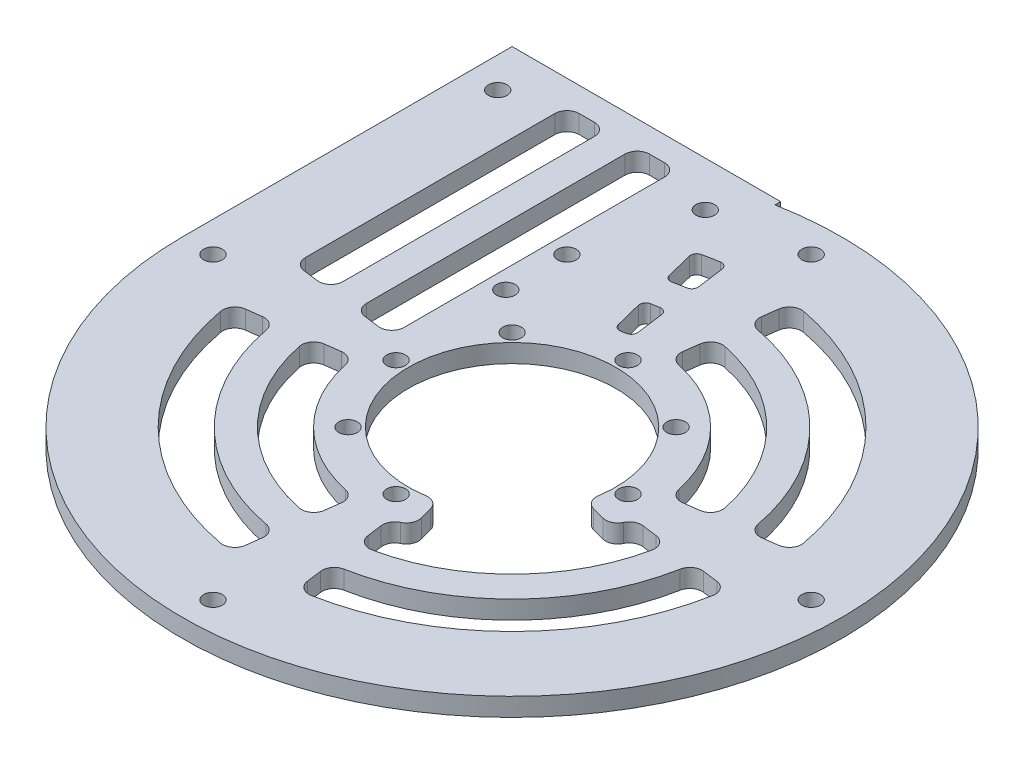
SolidWorks part; units mm, degrees
material "Thornel Mat VMA"
ref_plane "前视基准面" through (0, 0, 0) normal (0, 0, 1) x (1, 0, 0)
ref_plane "上视基准面" through (0, 0, 0) normal (0, 1, 0) x (1, 0, 0)
ref_plane "右视基准面" through (0, 0, 0) normal (1, 0, 0) x (0, 0, -1)
sketch "草图1" plane through (0, 0, 0) normal (0, 1, 0) x (1, 0, 0)
  line L0 (-54, 0) -> (-54, 54)
  line L1 (-54, 54) -> (-10, 54)
  line L2 (-10, 54) -> (-10, 53.066)
  line L3 (-32, 0) -> (-32, 54) construction
  line L4 (-15, 54) -> (-15, 46.6476) construction
  line L5 (-15, 54) -> (-15, 45.6644) construction
  line L6 (-49, 0) -> (-49, 54) construction
  line L7 (-10, 54) -> (-10, 45.6644) construction
  line L8 (-23, 0) -> (-23, 54) construction
  line L9 (-20, 28.98) -> (-20, 18.98) construction
  line L10 (-49, 46.6476) -> (-15, 46.6476) construction
  arc A0 (-54, 0) -> (-10, 53.066) centre (0, 0) ccw
  circle A1 centre (0, 0) radius 41 construction
  circle A2 centre (0, 0) radius 32 construction
  circle A3 centre (0, 0) radius 23 construction
  circle A4 centre (0, 0) radius 49 construction
  circle A5 centre (-15, 46.6476) radius 1.525
  circle A6 centre (0, 49) radius 1.525
  circle A7 centre (49, 0) radius 1.525
  circle A8 centre (0, -49) radius 1.525
  circle A9 centre (-49, 0) radius 1.525
  circle A10 centre (0, 0) radius 17
  circle A11 centre (0, 0) radius 19 construction
  circle A12 centre (0, 19) radius 1.525
  circle A13 centre (13.435, 13.435) radius 1.525
  circle A14 centre (19, 0) radius 1.525
  circle A15 centre (13.435, -13.435) radius 1.525
  circle A16 centre (0, -19) radius 1.525
  circle A17 centre (-13.435, -13.435) radius 1.525
  circle A18 centre (-19, 0) radius 1.525
  circle A19 centre (-13.435, 13.435) radius 1.525
  circle A20 centre (0, 0) radius 54 construction
  circle A21 centre (-49, 46.6476) radius 1.525
  circle A23 centre (-20, 28.98) radius 1.525
  circle A24 centre (-20, 18.98) radius 1.525
  circle A25 centre (44.7325, -20) radius 1.525 construction
  point P58 (-20, 24.98)
  dimension "D8" = 3.05
  dimension "D9" = 34
  dimension "D10" = 38
  dimension "D11" = 3.05
  dimension "D13" = 3
  dimension "D14" = 4
  dimension "D16" = 20
  dimension "D17" = 82
  dimension "D2" = 9
  dimension "D3" = 9
  dimension "D4" = 5
  dimension "D5" = 8
  dimension "D15" = 6
  dimension "D6" = 17
  dimension "D7" = 4
  dimension "D12" = 8
extrude "凸台-拉伸1" add sketch "草图1" along normal blind 3
sketch "草图2" plane through (0, 0, 0) normal (0, 1, 0) x (1, 0, 0)
  line L0 (-41, 7.1517) -> (-41, 48)
  line L1 (-39, 50) -> (-36.5, 50)
  line L2 (-23, 0) -> (-23, 54) construction
  line L3 (-23, 48) -> (-23, 5.3086)
  line L4 (-29.5, 0) -> (-29.5, 54)
  line L5 (-29.5, 5.6377) -> (-29.5, 48)
  line L6 (-34.5, 0) -> (-34.5, 54)
  line L7 (-34.5, 6.8226) -> (-34.5, 48)
  line L8 (-54, 54) -> (-10, 54) construction
  line L9 (-27.5, 50) -> (-25, 50)
  line L10 (-9.753, 38.7799) -> (-8.6551, 34.4142)
  line L11 (-3.7177, 28.2388) -> (-3.1299, 23.774)
  line L12 (0, 0) -> (-49, 0) construction
  line L13 (0, 0) -> (0, -49) construction
  line L14 (0, 0) -> (49, 0) construction
  line L15 (0, 0) -> (0, 29.5) construction
  line L16 (-5.2194, 39.6454) -> (-4.6318, 35.1823)
  line L17 (5.0838, 38.6155) -> (4.757, 36.1334)
  line L18 (-6.9469, 27.6223) -> (-5.8486, 23.255)
  line L19 (0, 34.5) -> (0, 49) construction
  line L20 (3.58, 27.1925) -> (3.2527, 24.7067)
  line L21 (38.6155, 5.0838) -> (36.1334, 4.757)
  line L22 (27.1925, 3.58) -> (24.7067, 3.2527)
  line L23 (38.6155, -5.0838) -> (36.1334, -4.757)
  line L24 (27.1925, -3.58) -> (24.7067, -3.2527)
  line L25 (5.0838, -38.6155) -> (4.757, -36.1334)
  line L26 (3.58, -27.1925) -> (3.2527, -24.7067)
  line L27 (-5.0838, -38.6155) -> (-4.757, -36.1334)
  line L28 (-3.58, -27.1925) -> (-3.2527, -24.7067)
  line L29 (-38.6155, -5.0838) -> (-36.1334, -4.757)
  line L30 (-27.1925, -3.58) -> (-24.7067, -3.2527)
  line L31 (-39.2611, 5.1688) -> (-36.7611, 4.8397)
  line L32 (-27.7611, 3.6548) -> (-25.2611, 3.3257)
  circle A0 centre (0, 0) radius 23 construction
  circle A1 centre (0, 0) radius 41 construction
  arc A2 (-22.49, -4.8167) -> (-4.8167, -22.49) centre (0, 0) ccw
  circle A3 centre (0, 0) radius 34.5
  arc A4 (-33.9067, -6.3706) -> (-6.3706, -33.9067) centre (0, 0) ccw
  circle A5 centre (0, 0) radius 29.5
  arc A6 (-28.8901, -5.9674) -> (-5.9674, -28.8901) centre (0, 0) ccw
  arc A7 (-40.3213, -7.4291) -> (-7.4291, -40.3213) centre (0, 0) ccw
  arc A8 (-6.3661, 40.5027) -> (-9.0028, 39.9994) centre (0, 0) ccw
  arc A9 (-5.4649, 34.0644) -> (-7.4688, 33.6818) centre (0, 0) ccw
  arc A10 (-4.8744, 29.0945) -> (-6.1869, 28.8439) centre (0, 0) ccw
  arc A11 (-3.9496, 22.6583) -> (-4.6755, 22.5198) centre (0, 0) ccw
  arc A12 (40.3213, 7.4291) -> (7.4291, 40.3213) centre (0, 0) ccw
  arc A13 (33.9067, 6.3706) -> (6.3706, 33.9067) centre (0, 0) ccw
  arc A14 (28.8901, 5.9674) -> (5.9674, 28.8901) centre (0, 0) ccw
  arc A15 (22.49, 4.8167) -> (4.8167, 22.49) centre (0, 0) ccw
  arc A16 (7.4291, -40.3213) -> (40.3213, -7.4291) centre (0, 0) ccw
  arc A17 (6.3706, -33.9067) -> (33.9067, -6.3706) centre (0, 0) ccw
  arc A18 (5.9674, -28.8901) -> (28.8901, -5.9674) centre (0, 0) ccw
  arc A19 (4.8167, -22.49) -> (22.49, -4.8167) centre (0, 0) ccw
  arc A20 (-39.2611, 5.1688) -> (-41, 7.1517) centre (-39, 7.1517) cw
  arc A21 (-36.7611, 4.8397) -> (-34.5, 6.8226) centre (-36.5, 6.8226) ccw
  arc A22 (-27.7611, 3.6548) -> (-29.5, 5.6377) centre (-27.5, 5.6377) cw
  arc A23 (-25.2611, 3.3257) -> (-23, 5.3086) centre (-25, 5.3086) ccw
  arc A24 (-23, 48) -> (-25, 50) centre (-25, 48) ccw
  arc A25 (-29.5, 48) -> (-27.5, 50) centre (-27.5, 48) cw
  arc A26 (-34.5, 48) -> (-36.5, 50) centre (-36.5, 48) ccw
  arc A27 (-41, 48) -> (-39, 50) centre (-39, 48) cw
  arc A28 (5.0838, -38.6155) -> (7.4291, -40.3213) centre (7.0667, -38.3544) ccw
  arc A29 (3.58, -27.1925) -> (5.9674, -28.8901) centre (5.5629, -26.9315) ccw
  arc A30 (3.2527, -24.7067) -> (4.8167, -22.49) centre (5.2356, -24.4456) cw
  arc A31 (4.757, -36.1334) -> (6.3706, -33.9067) centre (6.7399, -35.8723) cw
  arc A32 (-5.0838, -38.6155) -> (-7.4291, -40.3213) centre (-7.0667, -38.3544) cw
  arc A33 (-4.757, -36.1334) -> (-6.3706, -33.9067) centre (-6.7399, -35.8723) ccw
  arc A34 (-3.58, -27.1925) -> (-5.9674, -28.8901) centre (-5.5629, -26.9315) cw
  arc A35 (-3.2527, -24.7067) -> (-4.8167, -22.49) centre (-5.2356, -24.4456) ccw
  arc A36 (-24.7067, -3.2527) -> (-22.49, -4.8167) centre (-24.4456, -5.2356) cw
  arc A37 (-27.1925, -3.58) -> (-28.8901, -5.9674) centre (-26.9315, -5.5629) ccw
  arc A38 (-36.1334, -4.757) -> (-33.9067, -6.3706) centre (-35.8723, -6.7399) cw
  arc A39 (-38.6155, -5.0838) -> (-40.3213, -7.4291) centre (-38.3544, -7.0667) ccw
  arc A40 (-3.9496, 22.6583) -> (-3.1299, 23.774) centre (-4.1214, 23.6435) ccw
  arc A41 (-3.7177, 28.2388) -> (-4.8744, 29.0945) centre (-4.7092, 28.1083) ccw
  arc A42 (-4.6318, 35.1823) -> (-5.4649, 34.0644) centre (-5.6233, 35.0518) cw
  arc A43 (-5.2194, 39.6454) -> (-6.3661, 40.5027) centre (-6.2109, 39.5149) ccw
  arc A44 (-7.4688, 33.6818) -> (-8.6551, 34.4142) centre (-7.6853, 34.6581) cw
  arc A45 (-9.753, 38.7799) -> (-9.0028, 39.9994) centre (-8.7832, 39.0238) cw
  arc A46 (-6.1869, 28.8439) -> (-6.9469, 27.6223) centre (-5.9771, 27.8662) ccw
  arc A47 (-5.8486, 23.255) -> (-4.6755, 22.5198) centre (-4.8788, 23.4989) ccw
  arc A48 (38.6155, 5.0838) -> (40.3213, 7.4291) centre (38.3544, 7.0667) ccw
  arc A49 (36.1334, 4.757) -> (33.9067, 6.3706) centre (35.8723, 6.7399) cw
  arc A50 (27.1925, 3.58) -> (28.8901, 5.9674) centre (26.9315, 5.5629) ccw
  arc A51 (24.7067, 3.2527) -> (22.49, 4.8167) centre (24.4456, 5.2356) cw
  arc A52 (4.8167, 22.49) -> (3.2527, 24.7067) centre (5.2356, 24.4456) cw
  arc A53 (3.58, 27.1925) -> (5.9674, 28.8901) centre (5.5629, 26.9315) cw
  arc A54 (4.757, 36.1334) -> (6.3706, 33.9067) centre (6.7399, 35.8723) ccw
  arc A55 (5.0838, 38.6155) -> (7.4291, 40.3213) centre (7.0667, 38.3544) cw
  arc A56 (27.1925, -3.58) -> (28.8901, -5.9674) centre (26.9315, -5.5629) cw
  arc A57 (36.1334, -4.757) -> (33.9067, -6.3706) centre (35.8723, -6.7399) ccw
  arc A58 (38.6155, -5.0838) -> (40.3213, -7.4291) centre (38.3544, -7.0667) cw
  arc A59 (24.7067, -3.2527) -> (22.49, -4.8167) centre (24.4456, -5.2356) ccw
  point P81 (-23, 50)
  point P84 (-29.5, 50)
  point P115 (-3.0021, 22.8032)
  point P118 (-3.8505, 29.2476)
  point P121 (-4.5032, 34.2048)
  point P124 (-5.3516, 40.6492)
  point P129 (-10, 39.7618)
  point P132 (-7.1951, 28.6091)
  point P143 (22.8032, 3.0021)
  point P146 (3.0021, 22.8032)
  point P153 (5.3516, 40.6492)
  dimension "D8" = 2
  dimension "D9" = 2
  dimension "D10" = 1
  dimension "D11" = 2
  dimension "D12" = 2
  dimension "D5" = 4
  dimension "D6" = 15
  dimension "D1" = 2.5
  dimension "D2" = 2.5
  dimension "D3" = 2.5
  dimension "D4" = 2.5
  dimension "D7" = 4
extrude "切除-拉伸2" cut sketch "草图2" along normal through all
sketch "草图3" plane through (0, 3, 0) normal (0, 1, 0) x (1, 0, 0)
  line L0 (0, 0) -> (13.435, -13.435) construction
  line L1 (0, 0) -> (5.9528, -22.2163)
  line L2 (0, 0) -> (22.2163, -5.9528)
  arc A0 (4.8167, -22.49) -> (22.49, -4.8167) centre (0, 0) ccw construction
  arc A1 (5.9528, -22.2163) -> (22.2163, -5.9528) centre (0, 0) ccw
  dimension "D1" = 30
extrude "切除-拉伸3" cut sketch "草图3" against normal through all
fillet "圆角1" radius 2 4 edges at (5.9528, 1.5, 22.2163) (4.3999, 1.5, 16.4207) (16.4207, 1.5, 4.3999) (22.2163, 1.5, 5.9528)
sketch "草图5" plane through (0, 0, 0) normal (0, 1, 0) x (1, 0, 0)
  line L5 (-10, 54) -> (-54, 54) construction
  line L6 (-10, 54) -> (-10, 59) construction
  line L7 (-10, 59) -> (-54, 59) construction
  line L8 (-54, 54) -> (-54, 59) construction
  line L9 (-54, 54) -> (-54, 0) construction
  line L10 (-10, 54) -> (-10, 59) construction
  line L11 (-10, 59) -> (-20, 59) construction
  line L13 (-20, 54) -> (-10, 54) construction
  line L14 (-54, 54) -> (-54, 59) construction
  line L15 (-54, 59) -> (-44.9, 59) construction
  line L16 (-44.9, 59) -> (-44.9, 54) construction
  line L17 (-44.9, 54) -> (-54, 54) construction
  line L18 (-32, 54) -> (-32, 59) construction
  line L19 (-40.95, 59) -> (-35.05, 59)
  line L20 (-23.05, 54) -> (-28.95, 54) construction
  line L21 (-23.05, 54) -> (-23.05, 59) construction
  line L22 (-23.05, 59) -> (-28.95, 59) construction
  line L23 (-28.95, 54) -> (-28.95, 59) construction
  line L24 (-35.05, 54) -> (-35.05, 59) construction
  line L25 (-40.95, 54) -> (-35.05, 54)
  line L26 (-40.95, 54) -> (-40.95, 59)
  line L27 (-35.05, 54) -> (-28.95, 54) construction
  line L28 (-5, 51) -> (-20, 51)
  line L29 (-5, 51) -> (-5, 65.1)
  line L30 (-5, 65.1) -> (-20, 65.1)
  line L31 (-20, 51) -> (-20, 54)
  line L32 (-28.95, 59) -> (-35.05, 59) construction
  line L34 (-20, 59) -> (-20, 65.1)
  line L35 (-20, 59) -> (-20, 54)
  line L36 (-28.95, 54) -> (-23.05, 54) construction
  line L38 (-23.05, 59) -> (-28.95, 59) construction
  line L39 (-23.05, 54) -> (-23.05, 59) construction
  line L40 (-35.05, 54) -> (-35.05, 59)
  dimension "D2" = 17.9
  dimension "D3" = 6.1
  dimension "D4" = 5
  dimension "D5" = 3
  dimension "D6" = 11.1
  dimension "D7" = 15
  dimension "D8" = 3.05
extrude "凸台-拉伸3" [suppressed] add sketch "草图5" along normal up to surface (3 mm away)
sketch "草图6" [suppressed] plane through (0, 0, 0) normal (0, 1, 0) x (1, 0, 0)
  circle A0 centre (-22.95, 46.9) radius 1 construction
  circle A1 centre (-20, 54) radius 1
  circle A2 centre (-40.95, 54) radius 1
  circle A4 centre (-35.05, 54) radius 1
  dimension "D1" = 2
extrude "切除-拉伸7" [suppressed] cut sketch "草图6" along normal through all
